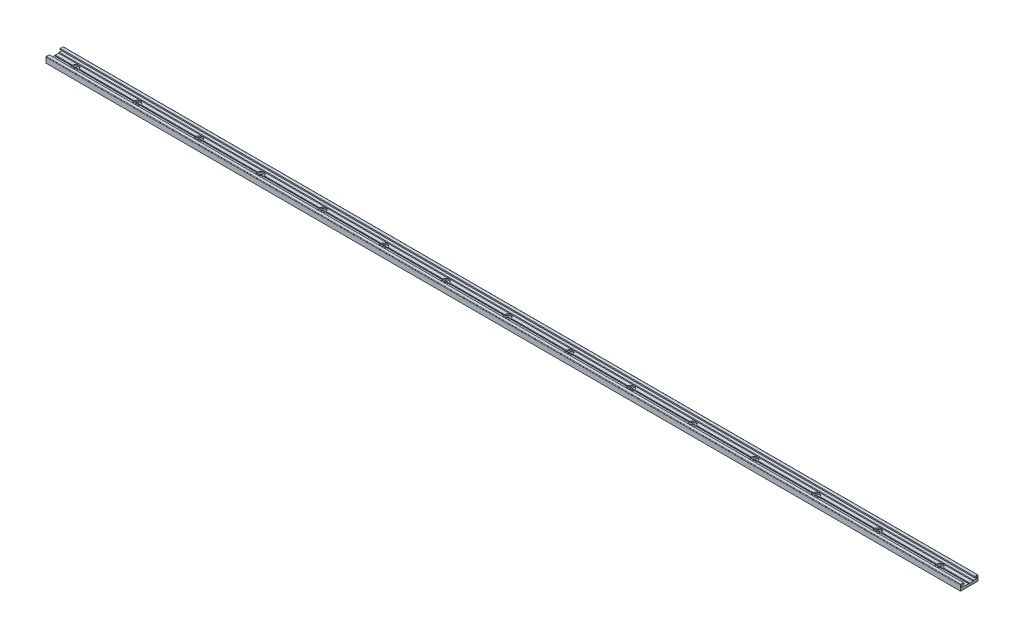
SolidWorks part; units mm, degrees
ref_plane "Front" through (0, 0, 0) normal (0, 0, 1) x (1, 0, 0)
ref_plane "Top" through (0, 0, 0) normal (0, 1, 0) x (1, 0, 0)
ref_plane "Right" through (0, 0, 0) normal (1, 0, 0) x (0, 0, -1)
sketch "Sketch1" plane through (0, 0, 0) normal (1, 0, 0) x (0, 0, -1)
  line L0 (0, -2.75) -> (0, 2.75) construction
  line L1 (-0.5, -0.45) -> (0, -0.7387) construction
  line L2 (-3.75, -0.45) -> (-0.5, -0.45) construction
  line L3 (-4.25, 0.05) -> (-3.75, -0.45) construction
  line L4 (-7.3, 0.05) -> (-4.25, 0.05) construction
  line L5 (-7.3, 1.55) -> (-7.3, 0.05) construction
  line L6 (-5.3, 1.55) -> (-7.3, 1.55) construction
  line L7 (-5.3, 2.75) -> (-5.3, 1.55) construction
  line L8 (-8, 2.75) -> (-5.3, 2.75) construction
  line L9 (-8.5, -2.75) -> (-8.5, 2.25) construction
  line L39 (-8.5, -2.75) -> (8.5, -2.75) construction
  line L40 (8.5, -2.75) -> (8.5, 2.25) construction
  line L41 (8, 2.75) -> (5.3, 2.75) construction
  line L42 (5.3, 2.75) -> (5.3, 1.55) construction
  line L43 (5.3, 1.55) -> (7.3, 1.55) construction
  line L44 (7.3, 1.55) -> (7.3, 0.05) construction
  line L45 (7.3, 0.05) -> (4.25, 0.05) construction
  line L46 (4.25, 0.05) -> (3.75, -0.45) construction
  line L47 (3.75, -0.45) -> (0.5, -0.45) construction
  line L48 (0.5, -0.45) -> (0, -0.7387) construction
  arc A0 (8, 2.75) -> (8.5, 2.25) centre (8, 2.25) cw construction
  arc A1 (-8, 2.75) -> (-8.5, 2.25) centre (-8, 2.25) ccw construction
  point P1 (7.3, 0.8)
  point P26 (0, 0)
  point P32 (0, -1.75)
  dimension "D12" = 0.5
  dimension "D1" = 30
  dimension "D3" = 2.3
  dimension "Rail Height" = 5.5
  dimension "D4" = 2.0113
  dimension "D5" = 2.8
  dimension "D7" = 1.2
  dimension "D8" = 3.2
  dimension "D9" = 1.2
  dimension "D10" = 45
  dimension "D11" = 3.75
  dimension "Rail Width" = 17
  dimension "Mounting Hole Depth" = 1
sketch "Sketch2" plane through (0, 0, 0) normal (0, 0, 1) x (1, 0, 0)
  line L0 (500, 0) -> (-500, 0) construction
  point P0 (-480, 0)
  point P3 (-420, 0)
  point P4 (0, 0)
  point P6 (-412, 0)
  point P7 (494, 0)
  dimension "Rail Length" = 1000
  dimension "Mounting Hole Ctr to End" = 20
  dimension "Mounting Hole Ctr to Ctr" = 60
  dimension "D2" = 6
  dimension "D1" = 8
sketch "Sketch5" plane through (0, 0, 0) normal (1, 0, 0) x (0, 0, -1)
  line L0 (-8.5, -2.75) -> (8.5, -2.75) construction
  line L1 (8.5, -2.75) -> (8.5, 2.25) construction
  line L2 (8, 2.75) -> (5.3, 2.75) construction
  line L3 (5.3, 2.75) -> (5.3, 1.55) construction
  line L4 (5.3, 1.55) -> (7.3, 1.55) construction
  line L5 (7.3, 1.55) -> (7.3, 0.05) construction
  line L6 (7.3, 0.05) -> (4.25, 0.05) construction
  line L7 (4.25, 0.05) -> (3.75, -0.45) construction
  line L8 (3.75, -0.45) -> (0.5, -0.45) construction
  line L9 (0.5, -0.45) -> (0, -0.7387) construction
  line L10 (-0.5, -0.45) -> (0, -0.7387) construction
  line L11 (-3.75, -0.45) -> (-0.5, -0.45) construction
  line L12 (-4.25, 0.05) -> (-3.75, -0.45) construction
  line L13 (-7.3, 0.05) -> (-4.25, 0.05) construction
  line L14 (-7.3, 1.55) -> (-7.3, 0.05) construction
  line L15 (-5.3, 1.55) -> (-7.3, 1.55) construction
  line L16 (-5.3, 2.75) -> (-5.3, 1.55) construction
  line L17 (-8, 2.75) -> (-5.3, 2.75) construction
  line L18 (-8.5, -2.75) -> (-8.5, 2.25) construction
  line L19 (-8.5, -2.75) -> (8.5, -2.75)
  line L20 (8.5, -2.75) -> (8.5, 2.25)
  line L21 (8, 2.75) -> (5.3, 2.75)
  line L22 (5.3, 2.75) -> (5.3, 1.55)
  line L23 (5.3, 1.55) -> (7.3, 1.55)
  line L24 (7.3, 1.55) -> (7.3, 0.05)
  line L25 (7.3, 0.05) -> (4.25, 0.05)
  line L26 (4.25, 0.05) -> (3.75, -0.45)
  line L27 (3.75, -0.45) -> (0.5, -0.45)
  line L28 (0.5, -0.45) -> (0, -0.7387)
  line L29 (-0.5, -0.45) -> (0, -0.7387)
  line L30 (-3.75, -0.45) -> (-0.5, -0.45)
  line L31 (-4.25, 0.05) -> (-3.75, -0.45)
  line L32 (-7.3, 0.05) -> (-4.25, 0.05)
  line L33 (-7.3, 1.55) -> (-7.3, 0.05)
  line L34 (-5.3, 1.55) -> (-7.3, 1.55)
  line L35 (-5.3, 2.75) -> (-5.3, 1.55)
  line L36 (-8, 2.75) -> (-5.3, 2.75)
  line L37 (-8.5, -2.75) -> (-8.5, 2.25)
  arc A0 (8.5, 2.25) -> (8, 2.75) centre (8, 2.25) ccw construction
  arc A1 (-8, 2.75) -> (-8.5, 2.25) centre (-8, 2.25) ccw construction
  arc A2 (8.5, 2.25) -> (8, 2.75) centre (8, 2.25) ccw
  arc A3 (-8, 2.75) -> (-8.5, 2.25) centre (-8, 2.25) ccw
extrude "Boss-Extrude1" add sketch "Sketch5" along normal up to vertex (500 mm away) and the other way up to vertex (500 mm away)
sketch "Sketch3" plane through (0, 0, 0) normal (0, 0, 1) x (1, 0, 0)
  line L0 (-483.25, -0.45) -> (-483.25, -1.75)
  line L1 (-483.25, -1.75) -> (-481.75, -1.75)
  line L2 (-481.75, -1.75) -> (-481.75, -2.75)
  line L3 (-481.75, -2.75) -> (-480, -2.75)
  line L4 (-480, -2.75) -> (-480, -0.45)
  line L5 (-480, -0.45) -> (-483.25, -0.45)
  line L8 (-483.25, -0.45) -> (-476.75, -0.45) construction
  line L10 (-478.25, -2.75) -> (-481.75, -2.75) construction
  line L19 (500, -2.75) -> (-500, -2.75) construction
  dimension "D1" = 1.3
  dimension "D2" = 6.5
  dimension "D3" = 3.5
revolve "Cut-Revolve1" cut sketch "Sketch3" angle 360 mid plane about L4
pattern_linear "LPattern1" count 17 spacing 60 along (1, 0, 0) of "Cut-Revolve1"
sketch "Sketch6" plane through (0, 2.75, 0) normal (0, 1, 0) x (1, 0, 0)
  line L1 (-500, 8.5) -> (389, 8.5)
  line L2 (-500, 8.5) -> (-500, -102.0657)
  line L3 (-500, -102.0657) -> (389, -102.0657)
  line L4 (389, 8.5) -> (389, -102.0657)
  line L5 (389, -102.0657) -> (557.8486, -102.0657)
  line L6 (389, -102.0657) -> (389, 126.2125)
  line L7 (389, 126.2125) -> (557.8486, 126.2125)
  line L8 (557.8486, -102.0657) -> (557.8486, 126.2125)
  line M2 (500, 8) -> (-500, 8)
  line M4 (-500, 5.3) -> (500, 5.3)
  line M5 (500, 5.3) -> (500, 8)
  dimension "D1" = 889
extrude "Cut-Extrude1" cut sketch "Sketch6" against normal through all contours L5 L8 L7 L6 L4 M2 M5 M4 | L4 M2 M4 M5
equation "\"D3@LPattern1\"=\"Mounting Hole Ctr to Ctr@Sketch2\""
equation "\"D2@Sketch2\"=\"Mounting Hole Ctr to End@Sketch2\"*.3"
equation "\"D1@Sketch2\"=\"Mounting Hole Ctr to End@Sketch2\"*.4"
